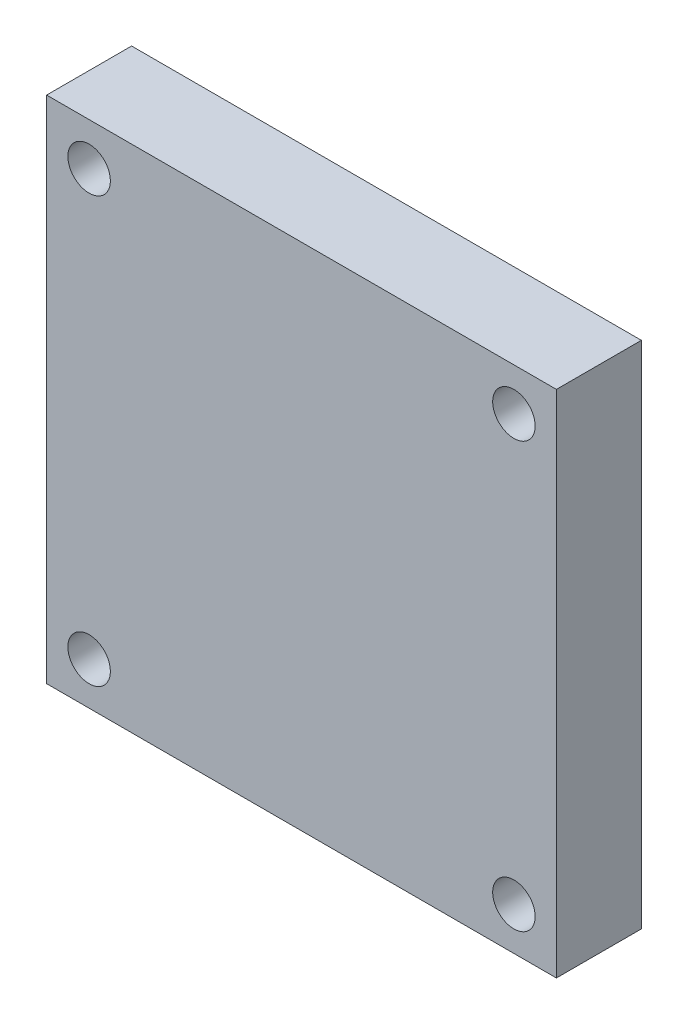
SolidWorks part; units mm, degrees
ref_plane "Front Plane" through (0, 0, 0) normal (0, 0, 1) x (1, 0, 0)
ref_plane "Top Plane" through (0, 0, 0) normal (0, 1, 0) x (1, 0, 0)
ref_plane "Right Plane" through (0, 0, 0) normal (1, 0, 0) x (0, 0, -1)
sketch "Sketch2" plane through (0, 0, 0) normal (0, 0, 1) x (1, 0, 0)
  line L1 (-30, -30) -> (30, -30)
  line L2 (-30, -30) -> (-30, 30)
  line L3 (-30, 30) -> (30, 30)
  line L4 (30, -30) -> (30, 30)
  line L5 (-30, -30) -> (30, 30) construction
  line L6 (-30, 30) -> (30, -30) construction
  circle A0 centre (-25, 25) radius 2.5
  circle A1 centre (25, 25) radius 2.5
  circle A2 centre (25, -25) radius 2.5
  circle A3 centre (-25, -25) radius 2.5
  point P0 (0, 0)
  point P17 (0, 0)
  dimension "D3" = 5
  dimension "D4" = 5
  dimension "D1" = 60
  dimension "D2" = 60
  dimension "D5" = 4
extrude "Boss-Extrude1" add sketch "Sketch2" along normal blind 10
sketch "Sketch3" [suppressed] plane through (0, 0, 0) normal (0, 0, 1) x (1, 0, 0)
  circle A0 centre (0, 0) radius 5
  dimension "D1" = 10
extrude "Motor Shaft Hole + Add Mounting Holes" [suppressed] cut sketch "Sketch3" against normal through all both and the other way through all
